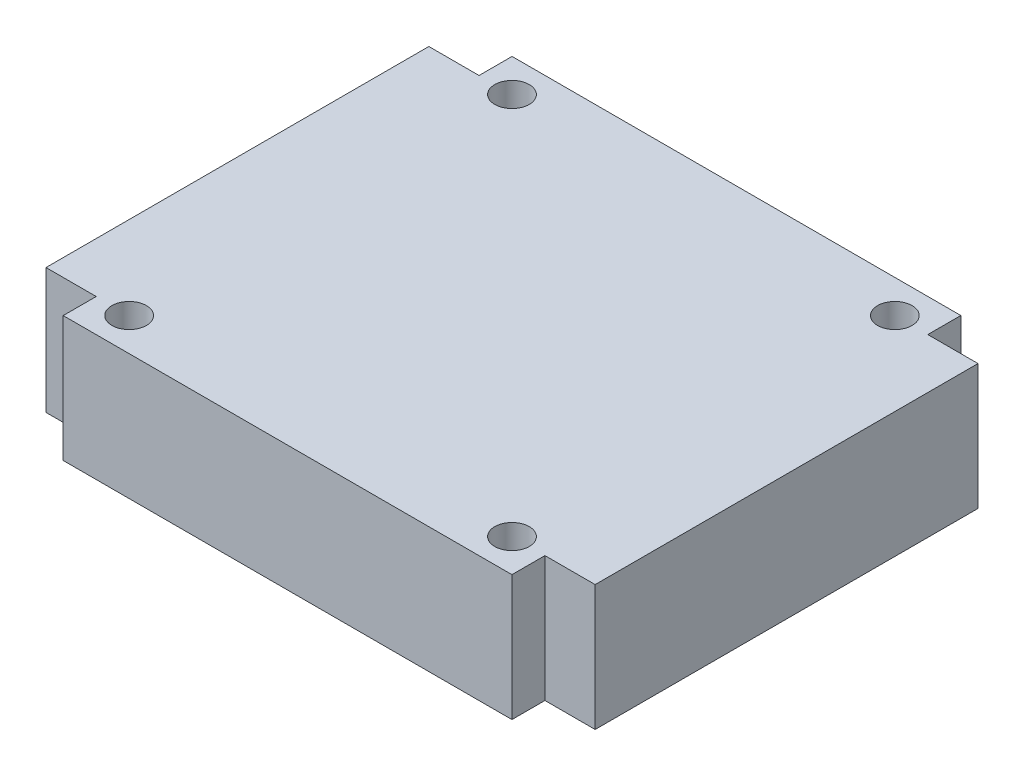
SolidWorks part; units mm, degrees
ref_plane "Front Plane" through (0, 0, 0) normal (0, 0, 1) x (1, 0, 0)
ref_plane "Top Plane" through (0, 0, 0) normal (0, 1, 0) x (1, 0, 0)
ref_plane "Right Plane" through (0, 0, 0) normal (1, 0, 0) x (0, 0, -1)
sketch "Sketch1" plane through (0, 0, 0) normal (0, 1, 0) x (1, 0, 0)
  line L0 (-15.25, 15.25) -> (15.25, 15.25) construction
  line L1 (-15.25, 15.25) -> (-15.25, -15.25) construction
  circle A0 centre (-15.25, 15.25) radius 1.375
  circle A1 centre (15.25, 15.25) radius 1.375
  circle A2 centre (15.25, -15.25) radius 1.375
  circle A3 centre (-15.25, -15.25) radius 1.375
  point P10 (0, 15.25)
  point P12 (-15.25, 0)
  dimension "D1" = 2.75
  dimension "D2" = 30.5
  dimension "D3" = 30.5
sketch "Sketch2" plane through (0, 0, 0) normal (0, 1, 0) x (1, 0, 0)
  line L0 (17.875, 15.25) -> (21.875, 15.25)
  line L1 (17.875, -15.25) -> (21.875, -15.25)
  line L2 (-17.875, -17.88) -> (17.875, -17.88)
  line L3 (-17.875, -17.88) -> (-17.875, -15.25)
  line L4 (-17.875, 17.88) -> (17.875, 17.88)
  line L5 (17.875, -17.88) -> (17.875, -15.25)
  line L6 (-17.875, -17.88) -> (17.875, 17.88) construction
  line L7 (-17.875, 17.88) -> (17.875, -17.88) construction
  line L8 (21.875, 15.25) -> (21.875, -15.25)
  line L9 (17.875, 15.25) -> (17.875, 17.88)
  line L10 (0, 12.9542) -> (0, -12.1546) construction
  line L11 (-17.875, -15.25) -> (-21.875, -15.25)
  line L12 (-21.875, 15.25) -> (-21.875, -15.25)
  line L13 (-17.875, 15.25) -> (-21.875, 15.25)
  line L14 (-17.875, 15.25) -> (-17.875, 17.88)
  circle A1 centre (15.25, 15.25) radius 1.375 construction
  point P4 (0, 0)
  dimension "D1" = 2.625
  dimension "D2" = 2.63
  dimension "D3" = 4
extrude "Boss-Extrude1" add sketch "Sketch2" along normal blind 10
extrude "Cut-Extrude1" cut sketch "Sketch1" along normal through all both and the other way through all
